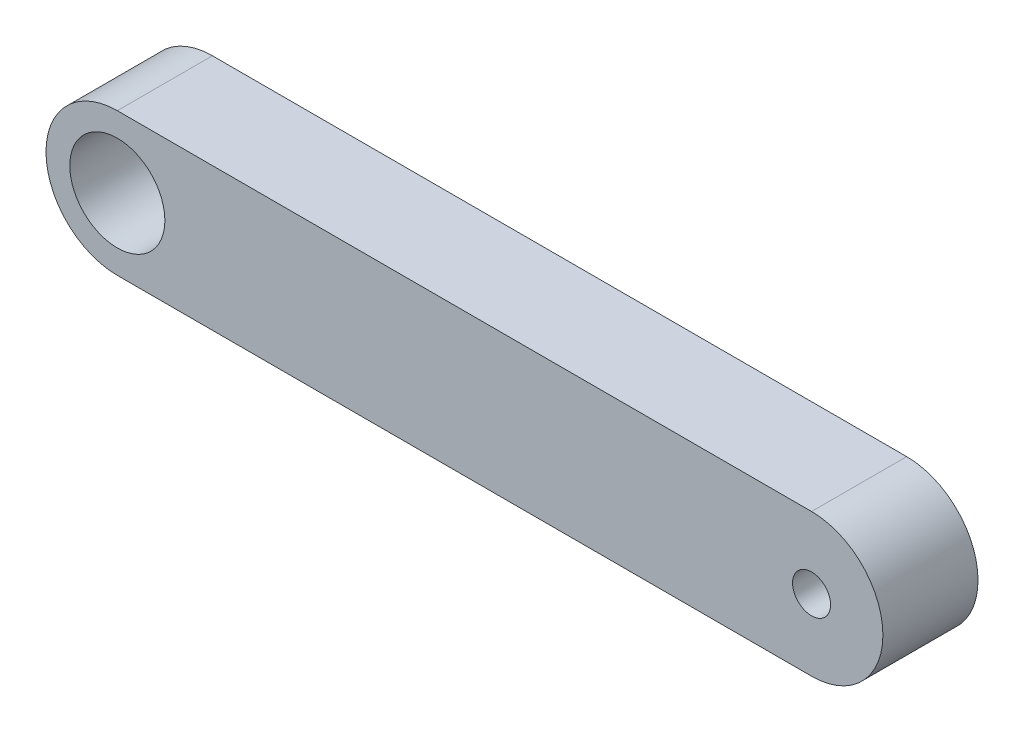
SolidWorks part; units mm, degrees
ref_plane "Front Plane" through (0, 0, 0) normal (0, 0, 1) x (1, 0, 0)
ref_plane "Top Plane" through (0, 0, 0) normal (0, 1, 0) x (1, 0, 0)
ref_plane "Right Plane" through (0, 0, 0) normal (1, 0, 0) x (0, 0, -1)
sketch "Esquisse1" plane through (0, 0, 0) normal (0, 0, 1) x (1, 0, 0)
  line L0 (0, 0) -> (-73, 0) construction
  line L1 (0, -7.5) -> (-73, -7.5)
  line L2 (0, 7.5) -> (-73, 7.5)
  arc A0 (0, -7.5) -> (0, 7.5) centre (0, 0) ccw
  arc A1 (-73, 7.5) -> (-73, -7.5) centre (-73, 0) ccw
  point P3 (-36.5, 0)
  point P8 (-80.5, 0)
  point P9 (7.5, 0)
  dimension "D1" = 15
  dimension "D2" = 88
extrude "Boss.-Extru.1" add sketch "Esquisse1" along normal blind 10
sketch "Esquisse2" plane through (0, 0, 10) normal (0, 0, 1) x (1, 0, 0)
  circle A0 centre (-73, 0) radius 5
  circle A1 centre (0, 0) radius 2
  dimension "D1" = 10
  dimension "D2" = 4
extrude "Enlèv. mat.-Extru.1" cut sketch "Esquisse2" against normal through all
